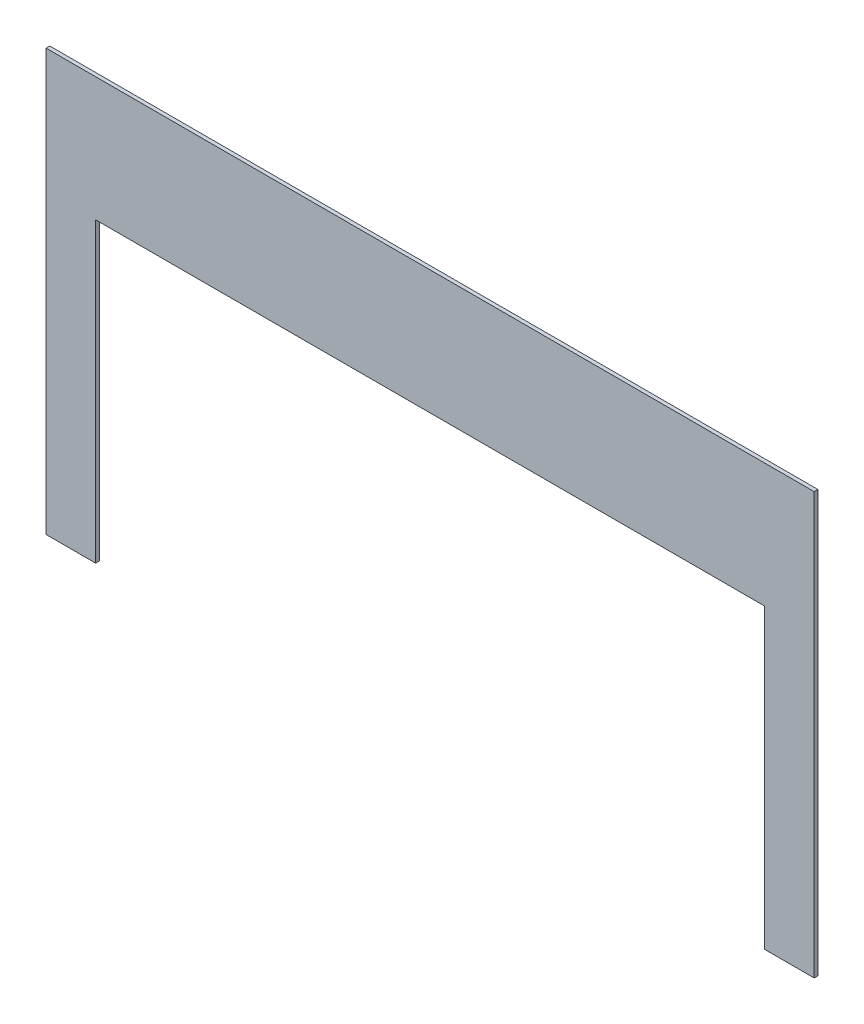
SolidWorks part; units mm, degrees
ref_plane "Front Plane" through (0, 0, 0) normal (0, 0, 1) x (1, 0, 0)
ref_plane "Top Plane" through (0, 0, 0) normal (0, 1, 0) x (1, 0, 0)
ref_plane "Right Plane" through (0, 0, 0) normal (1, 0, 0) x (0, 0, -1)
other "Configuration Table"
sketch "Sketch1" plane through (0, 0, 0) normal (0, 0, 1) x (1, 0, 0)
  line L1 (30, 1780) -> (340, 1780)
  line L2 (30, 1780) -> (30, 1950)
  line L3 (30, 1950) -> (340, 1950)
  line L4 (340, 1780) -> (340, 1950)
extrude "PRESS_panel_ust_sol_1" add sketch "Sketch1" along normal blind 1.5 from offset 38.5 separate body
sketch "Sketch2" plane through (0, 0, 0) normal (0, 0, 1) x (1, 0, 0)
  line L1 (50, 1760) -> (320, 1760)
  line L2 (50, 1760) -> (50, 1900)
  line L3 (50, 1900) -> (320, 1900)
  line L4 (320, 1760) -> (320, 1900)
extrude "PRESS_panel_ust_sol_2" cut sketch "Sketch2" along normal blind 3.5 from offset 37.5
